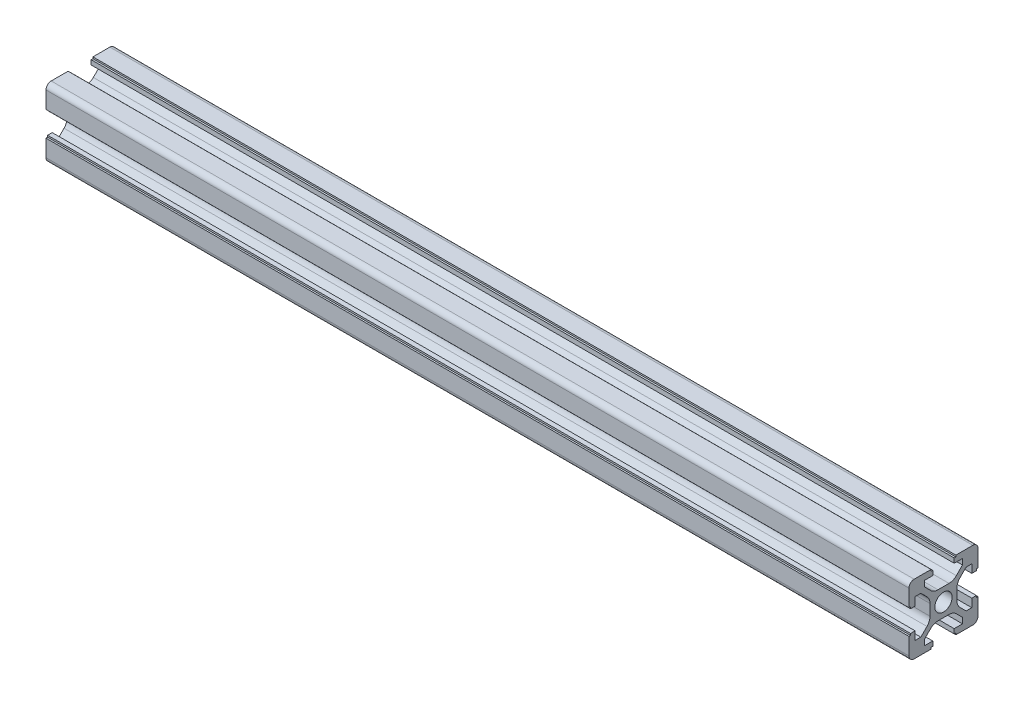
SolidWorks part; units mm, degrees
ref_plane "前视基准面" through (0, 0, 0) normal (0, 0, 1) x (1, 0, 0)
ref_plane "上视基准面" through (0, 0, 0) normal (0, 1, 0) x (1, 0, 0)
ref_plane "右视基准面" through (0, 0, 0) normal (1, 0, 0) x (0, 0, -1)
sketch "草图1" plane through (0, 0, 0) normal (1, 0, 0) x (0, 0, -1)
  line L0 (0, 0) -> (-10, 0) construction
  line L1 (0, 0) -> (0, 10) construction
  line L2 (0, 0) -> (-10, 10) construction
  line L3 (-10, 10) -> (-10, 3.6)
  line L4 (-10, 3.6) -> (-9.531, 3.6)
  line L5 (-9.531, 3.6) -> (-9.531, 3.1)
  line L6 (-9.531, 3.1) -> (-8.2, 3.1)
  line L7 (-8.2, 3.1) -> (-8.2, 5.5)
  line L8 (-8.2, 5.5) -> (-6.5607, 5.5)
  line L9 (-6.5607, 5.5) -> (-3.9, 2.8393)
  line L10 (-3.9, 2.8393) -> (-3.9, 0)
  line L11 (-3.6, 9.531) -> (-3.1, 9.531)
  line L12 (-2.8393, 3.9) -> (0, 3.9)
  line L13 (-5.5, 6.5607) -> (-2.8393, 3.9)
  line L14 (-5.5, 8.2) -> (-5.5, 6.5607)
  line L15 (-3.1, 8.2) -> (-5.5, 8.2)
  line L16 (-3.1, 9.531) -> (-3.1, 8.2)
  line L17 (-3.6, 10) -> (-3.6, 9.531)
  line L18 (-10, 10) -> (-3.6, 10)
  line L19 (0, 0) -> (0, 10) construction
  line L20 (0, 0) -> (10, 0) construction
  line L21 (0, 0) -> (10, 10) construction
  line L22 (10, 10) -> (3.6, 10)
  line L23 (3.6, 10) -> (3.6, 9.531)
  line L24 (3.6, 9.531) -> (3.1, 9.531)
  line L25 (3.1, 9.531) -> (3.1, 8.2)
  line L26 (3.1, 8.2) -> (5.5, 8.2)
  line L27 (5.5, 8.2) -> (5.5, 6.5607)
  line L28 (5.5, 6.5607) -> (2.8393, 3.9)
  line L29 (2.8393, 3.9) -> (0, 3.9)
  line L30 (9.531, 3.6) -> (9.531, 3.1)
  line L31 (3.9, 2.8393) -> (3.9, 0)
  line L32 (6.5607, 5.5) -> (3.9, 2.8393)
  line L33 (8.2, 5.5) -> (6.5607, 5.5)
  line L34 (8.2, 3.1) -> (8.2, 5.5)
  line L35 (9.531, 3.1) -> (8.2, 3.1)
  line L36 (10, 3.6) -> (9.531, 3.6)
  line L37 (10, 10) -> (10, 3.6)
  line L38 (0, 0) -> (10, 0) construction
  line L39 (0, 0) -> (0, -10) construction
  line L40 (0, 0) -> (10, -10) construction
  line L41 (10, -10) -> (10, -3.6)
  line L42 (10, -3.6) -> (9.531, -3.6)
  line L43 (9.531, -3.6) -> (9.531, -3.1)
  line L44 (9.531, -3.1) -> (8.2, -3.1)
  line L45 (8.2, -3.1) -> (8.2, -5.5)
  line L46 (8.2, -5.5) -> (6.5607, -5.5)
  line L47 (6.5607, -5.5) -> (3.9, -2.8393)
  line L48 (3.9, -2.8393) -> (3.9, 0)
  line L49 (3.6, -9.531) -> (3.1, -9.531)
  line L50 (2.8393, -3.9) -> (0, -3.9)
  line L51 (5.5, -6.5607) -> (2.8393, -3.9)
  line L52 (5.5, -8.2) -> (5.5, -6.5607)
  line L53 (3.1, -8.2) -> (5.5, -8.2)
  line L54 (3.1, -9.531) -> (3.1, -8.2)
  line L55 (3.6, -10) -> (3.6, -9.531)
  line L56 (10, -10) -> (3.6, -10)
  line L57 (0, 0) -> (0, -10) construction
  line L58 (0, 0) -> (-10, 0) construction
  line L59 (0, 0) -> (-10, -10) construction
  line L60 (-10, -10) -> (-3.6, -10)
  line L61 (-3.6, -10) -> (-3.6, -9.531)
  line L62 (-3.6, -9.531) -> (-3.1, -9.531)
  line L63 (-3.1, -9.531) -> (-3.1, -8.2)
  line L64 (-3.1, -8.2) -> (-5.5, -8.2)
  line L65 (-5.5, -8.2) -> (-5.5, -6.5607)
  line L66 (-5.5, -6.5607) -> (-2.8393, -3.9)
  line L67 (-2.8393, -3.9) -> (0, -3.9)
  line L68 (-9.531, -3.6) -> (-9.531, -3.1)
  line L69 (-3.9, -2.8393) -> (-3.9, 0)
  line L70 (-6.5607, -5.5) -> (-3.9, -2.8393)
  line L71 (-8.2, -5.5) -> (-6.5607, -5.5)
  line L72 (-8.2, -3.1) -> (-8.2, -5.5)
  line L73 (-9.531, -3.1) -> (-8.2, -3.1)
  line L74 (-10, -3.6) -> (-9.531, -3.6)
  line L75 (-10, -10) -> (-10, -3.6)
  arc A0 (0, 2.5) -> (-2.5, 0) centre (0, 0) ccw
  arc A1 (2.5, 0) -> (0, 2.5) centre (0, 0) ccw
  arc A2 (0, -2.5) -> (2.5, 0) centre (0, 0) ccw
  arc A3 (-2.5, 0) -> (0, -2.5) centre (0, 0) ccw
  point P89 (0, 0)
  dimension "D3" = 5
  dimension "D1" = 10
  dimension "D2" = 10
  dimension "D4" = 10
  dimension "D5" = 1.8
  dimension "D6" = 5.5
  dimension "D7" = 3.1
  dimension "D8" = 3.6
  dimension "D9" = 6.1
  dimension "D10" = 0.75
  dimension "D11" = 4
extrude "凸台-拉伸1" add sketch "草图1" along normal blind 250
fillet "圆角1" radius 1.5 4 edges at (125, -10, -10) (125, -10, 10) (125, 10, -10) (125, 10, 10)
fillet "圆角2" radius 3 8 edges at (125, -3.9, 2.8393) (125, -3.9, -2.8393) (125, -2.8393, -3.9) (125, 2.8393, -3.9) (125, 2.8393, 3.9) (125, -2.8393, 3.9) (125, 3.9, 2.8393) (125, 3.9, -2.8393)
